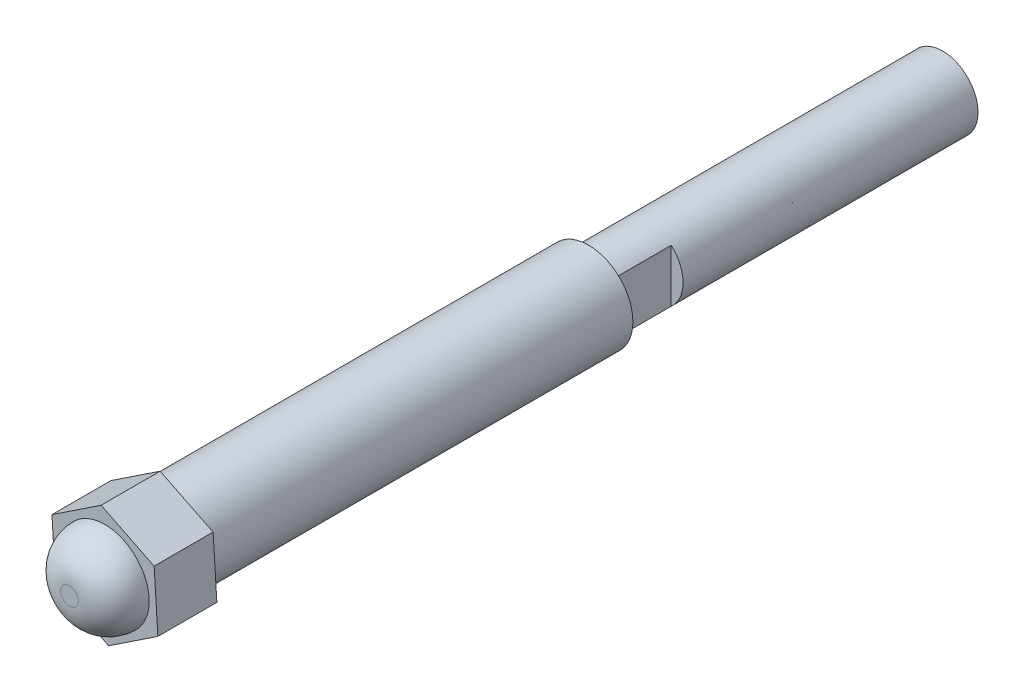
SolidWorks part; units mm, degrees
material "AISI 316 Stainless Steel Sheet (SS)"
ref_plane "Front Plane" through (0, 0, 0) normal (0, 0, 1) x (1, 0, 0)
ref_plane "Top Plane" through (0, 0, 0) normal (0, 1, 0) x (1, 0, 0)
ref_plane "Right Plane" through (0, 0, 0) normal (1, 0, 0) x (0, 0, -1)
sketch "Sketch1" plane through (0, 0, 0) normal (0, 0, 1) x (1, 0, 0)
  circle A0 centre (0, 0) radius 4.7625
  dimension "D1" = 9.525
extrude "Boss-Extrude1" add sketch "Sketch1" along normal blind 55.88
sketch "Sketch2" plane through (0, 0, 0) normal (0, 0, -1) x (-1, 0, 0)
  circle A0 centre (0, 0) radius 3.81
  dimension "D1" = 7.62
extrude "Boss-Extrude2" add sketch "Sketch2" along normal blind 38.1
sketch "Sketch3" plane through (0, 0, 0) normal (0, 1, 0) x (1, 0, 0)
  line L0 (-3.81, 0) -> (-3.81, 6.35)
  line L1 (-3.81, 38.1) -> (-3.81, 0) construction
  line L2 (-3.81, 6.35) -> (-2.54, 6.35)
  line L3 (-2.54, 6.35) -> (-2.54, 0)
  line L4 (4.7625, 0) -> (-4.7625, 0) construction
  line L5 (-3.81, 0) -> (-2.54, 0)
  line L6 (0, 0) -> (0, 9.0711) construction
  line L7 (3.81, 0) -> (2.54, 0)
  line L8 (3.81, 6.35) -> (2.54, 6.35)
  line L9 (3.81, 0) -> (3.81, 6.35)
  line L10 (2.54, 6.35) -> (2.54, 0)
  dimension "D1" = 6.35
  dimension "D2" = 1.27
extrude "Cut-Extrude1" cut sketch "Sketch3" against normal mid plane 38.1
sketch "Sketch4" plane through (0, 0, -38.1) normal (0, 0, -1) x (-1, 0, 0)
  circle A0 centre (0, 0) radius 1.5875
  dimension "D1" = 3.175
extrude "Cut-Extrude2" cut sketch "Sketch4" against normal up to surface (38.1 mm away) up to face at (0, 0, 0)
fillet "Fillet2" radius 3.81 1 edges at (4.7625, 0, 55.88)
sketch "Sketch7" plane through (0, 0, 0) normal (0, 0, 1) x (1, 0, 0)
  line L1 (5.7015, -2.8247) -> (5.297, 3.5253)
  line L2 (5.297, 3.5253) -> (-0.4045, 6.35)
  line L3 (-0.4045, 6.35) -> (-5.7015, 2.8247)
  line L4 (-5.7015, 2.8247) -> (-5.297, -3.5253)
  line L5 (-5.297, -3.5253) -> (0.4045, -6.35)
  line L6 (0.4045, -6.35) -> (5.7015, -2.8247)
  circle A0 centre (0, 0) radius 5.5104 construction
  dimension "D1" = 6.35
extrude "Boss-Extrude3" add sketch "Sketch7" along normal blind 6.35 from offset 45.72
